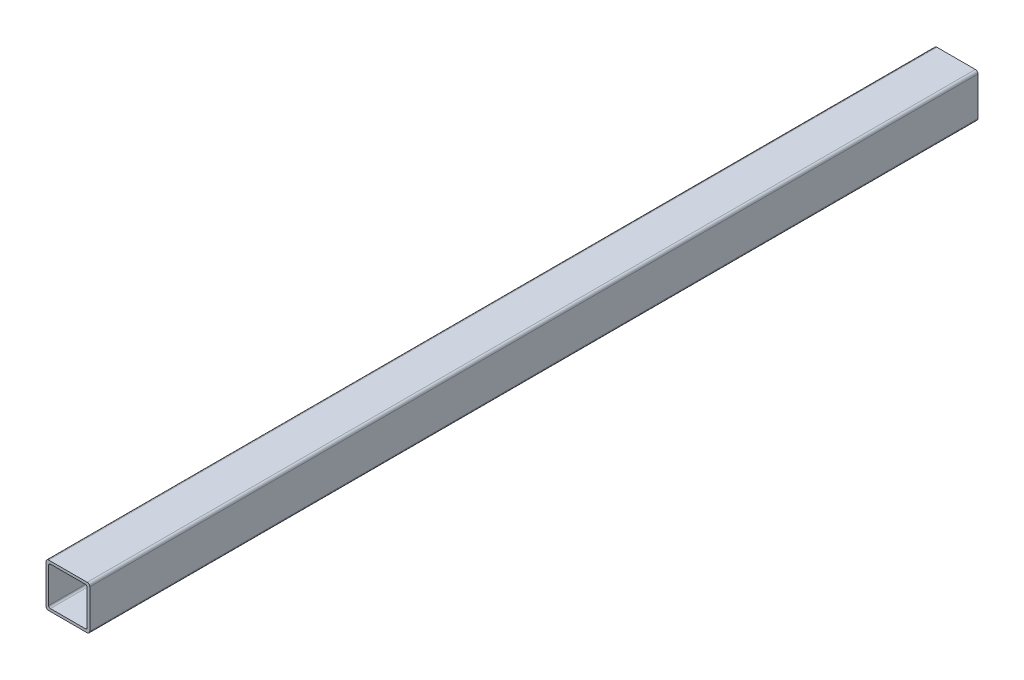
SolidWorks part; units mm, degrees
material "AISI 1020"
ref_plane "Спереди" through (0, 0, 0) normal (0, 0, 1) x (1, 0, 0)
ref_plane "Сверху" through (0, 0, 0) normal (0, 1, 0) x (1, 0, 0)
ref_plane "Справа" through (0, 0, 0) normal (1, 0, 0) x (0, 0, -1)
sketch "Эскиз1" plane through (0, 0, 0) normal (0, 0, 1) x (1, 0, 0)
  line B0 (-22, 25) -> (22, 25)
  line B1 (-25, 22) -> (-25, -22)
  line B2 (-22, -25) -> (22, -25)
  line B3 (25, 22) -> (25, -22)
  line B4 (-20, 22) -> (20, 22)
  line B5 (-22, 20) -> (-22, -20)
  line B6 (-20, -22) -> (20, -22)
  line B7 (22, 20) -> (22, -20)
  arc B8 (-25, -22) -> (-22, -25) centre (-22, -22) ccw
  arc B9 (22, -25) -> (25, -22) centre (22, -22) ccw
  arc B10 (22, 25) -> (25, 22) centre (22, 22) cw
  arc B11 (-22, 25) -> (-25, 22) centre (-22, 22) ccw
  arc B12 (-22, -20) -> (-20, -22) centre (-20, -20) ccw
  arc B13 (20, -22) -> (22, -20) centre (20, -20) ccw
  arc B14 (20, 22) -> (22, 20) centre (20, 20) cw
  arc B15 (-20, 22) -> (-22, 20) centre (-20, 20) ccw
sketch_block_instance "Труба профильная 50х50х3-1"
sketch_block "Труба профильная 50х50х3" parameters "D3"=3, "D4"=2, "D1"=50, "D2"=3
extrude "Бобышка-Вытянуть1" add sketch "Эскиз1" against normal up to surface (1015 mm away)
